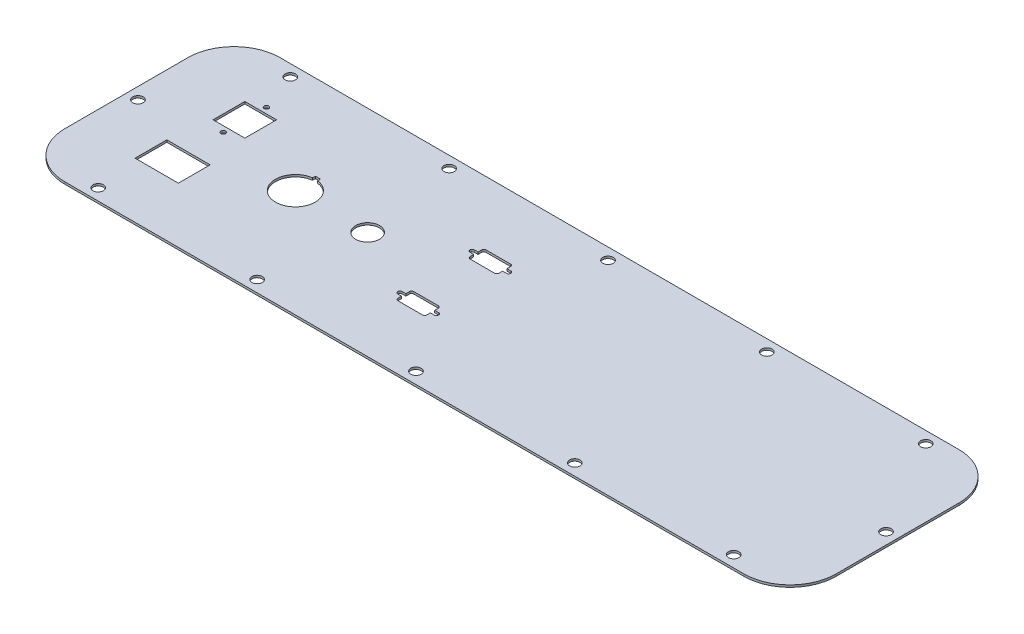
SolidWorks part; units mm, degrees
ref_plane "Front Plane" through (0, 0, 0) normal (0, 0, 1) x (1, 0, 0)
ref_plane "Top Plane" through (0, 0, 0) normal (0, 1, 0) x (1, 0, 0)
ref_plane "Right Plane" through (0, 0, 0) normal (1, 0, 0) x (0, 0, -1)
sketch "Sketch1" plane through (0, 0, 0) normal (0, 1, 0) x (1, 0, 0)
  line L0 (0, 0) -> (-259, 0) construction
  line L1 (235, -74.5) -> (-235, -74.5)
  line L2 (267, -42.5) -> (267, 42.5)
  line L3 (235, 74.5) -> (-235, 74.5)
  line L4 (-267, -42.5) -> (-267, 42.5)
  line L5 (267, -74.5) -> (-267, 74.5) construction
  line L6 (267, 74.5) -> (-267, -74.5) construction
  line L7 (0, 0) -> (259, 0) construction
  line L8 (220, 66.5) -> (-220, 66.5) construction
  line L9 (0, 66.5) -> (0, 0) construction
  line L10 (-220, 66.5) -> (-110, 66.5) construction
  arc A0 (-235, -74.5) -> (-267, -42.5) centre (-235, -42.5) cw
  arc A1 (267, -42.5) -> (235, -74.5) centre (235, -42.5) cw
  arc A2 (235, 74.5) -> (267, 42.5) centre (235, 42.5) cw
  arc A3 (-235, 74.5) -> (-267, 42.5) centre (-235, 42.5) ccw
  circle A4 centre (-259, 0) radius 3.6
  circle A5 centre (259, 0) radius 3.6
  circle A6 centre (-220, 66.5) radius 3.6
  circle A7 centre (-110, 66.5) radius 3.6
  circle A8 centre (0, 66.5) radius 3.6
  circle A9 centre (110, 66.5) radius 3.6
  circle A10 centre (220, 66.5) radius 3.6
  circle A11 centre (220, -66.5) radius 3.6
  circle A12 centre (110, -66.5) radius 3.6
  circle A13 centre (0, -66.5) radius 3.6
  circle A14 centre (-110, -66.5) radius 3.6
  circle A15 centre (-220, -66.5) radius 3.6
  point P0 (0, 0)
  point P26 (0, 66.5)
  dimension "D3" = 32
  dimension "D4" = 7.2
  dimension "D1" = 534
  dimension "D2" = 149
  dimension "D5" = 259
  dimension "D6" = 66.5
  dimension "D7" = 440
  dimension "D9" = 110
  dimension "D8" = 5
extrude "Boss-Extrude1" add sketch "Sketch1" along normal blind 1.5
sketch "Sketch2" plane through (0, 0, 0) normal (0, 1, 0) x (1, 0, 0)
  line L0 (-210, 25) -> (-210, -25) construction
  line L1 (-221, 14) -> (-199, 14)
  line L2 (-221, 14) -> (-221, 36)
  line L3 (-221, 36) -> (-199, 36)
  line L4 (-199, 14) -> (-199, 36)
  line L5 (-221, 14) -> (-199, 36) construction
  line L6 (-221, 36) -> (-199, 14) construction
  line L7 (-210, 10) -> (-210, 40) construction
  line L8 (-210, 14) -> (-210, 36) construction
  line L9 (-150, 0) -> (-150, 15.6382) construction
  line L10 (-210, -14) -> (-210, -36) construction
  line L11 (-151.75, 15.6382) -> (-148.25, 15.6382)
  line L12 (-151.75, 15.6382) -> (-151.75, 13.6382)
  line L14 (-148.25, 15.6382) -> (-148.25, 13.6382)
  line L15 (-195, -36) -> (-225, -36)
  line L16 (-195, -36) -> (-195, -14)
  line L17 (-195, -14) -> (-225, -14)
  line L18 (-225, -36) -> (-225, -14)
  line L19 (-195, -36) -> (-225, -14) construction
  line L20 (-195, -14) -> (-225, -36) construction
  line L21 (-40, 25) -> (-40, -25) construction
  line L23 (-210, 0) -> (0, 0) construction
  circle A0 centre (-210, 10) radius 1.6
  circle A1 centre (-210, 40) radius 1.6
  arc A2 (-151.75, 13.6382) -> (-148.25, 13.6382) centre (-150, 0) ccw
  arc A3 (-151.75, 13.6382) -> (-148.25, 13.6382) centre (-150, 0) cw construction
  circle A4 centre (-100, 0) radius 8.25
  point P0 (-210, 25)
  point P11 (-210, 25)
  point P22 (-150, 15.6382)
  point P32 (-210, 25)
  point P33 (-210, 0)
  point P37 (-40, 0)
  point P38 (-53.1341, 25)
  line B0 (-40, 19.5) -> (-40, 30.5) construction
  line B1 (-31.5, 30.5) -> (-48.5, 30.5)
  line B2 (-48.5, 19.5) -> (-31.5, 19.5)
  line B3 (-40, 25) -> (-50, 25) construction
  line B4 (-52.6, 26.5) -> (-50, 26.5)
  line B5 (-52.6, 23.5) -> (-50, 23.5)
  line B6 (-50, 23.5) -> (-50, 21)
  line B7 (-50, 26.5) -> (-50, 29)
  line B8 (-30, 23.5) -> (-30, 21)
  line B9 (-27.4, 23.5) -> (-30, 23.5)
  line B10 (-27.4, 26.5) -> (-30, 26.5)
  line B11 (-30, 26.5) -> (-30, 29)
  arc B12 (-52.6, 26.5) -> (-52.6, 23.5) centre (-52.6, 25) ccw
  arc B13 (-50, 21) -> (-48.5, 19.5) centre (-48.5, 21) ccw
  arc B14 (-48.5, 30.5) -> (-50, 29) centre (-48.5, 29) ccw
  arc B15 (-30, 21) -> (-31.5, 19.5) centre (-31.5, 21) cw
  arc B16 (-27.4, 26.5) -> (-27.4, 23.5) centre (-27.4, 25) cw
  arc B17 (-31.5, 30.5) -> (-30, 29) centre (-31.5, 29) cw
  line B18 (-31.5, -19.5) -> (-48.5, -19.5)
  line B19 (-48.5, -30.5) -> (-31.5, -30.5)
  line B20 (-40, -25) -> (-50, -25) construction
  line B21 (-52.6, -23.5) -> (-50, -23.5)
  line B22 (-52.6, -26.5) -> (-50, -26.5)
  line B23 (-50, -26.5) -> (-50, -29)
  line B24 (-50, -23.5) -> (-50, -21)
  line B25 (-30, -26.5) -> (-30, -29)
  line B26 (-27.4, -26.5) -> (-30, -26.5)
  line B27 (-27.4, -23.5) -> (-30, -23.5)
  line B28 (-30, -23.5) -> (-30, -21)
  arc B29 (-52.6, -23.5) -> (-52.6, -26.5) centre (-52.6, -25) ccw
  arc B30 (-50, -29) -> (-48.5, -30.5) centre (-48.5, -29) ccw
  arc B31 (-48.5, -19.5) -> (-50, -21) centre (-48.5, -21) ccw
  arc B32 (-30, -29) -> (-31.5, -30.5) centre (-31.5, -29) cw
  arc B33 (-27.4, -23.5) -> (-27.4, -26.5) centre (-27.4, -25) cw
  arc B34 (-31.5, -19.5) -> (-30, -21) centre (-31.5, -21) cw
  dimension "D4" = 3.2
  dimension "D6" = 27.5
  dimension "D13" = 16.5
  dimension "D1" = 22
  dimension "D2" = 22
  dimension "D3" = 210
  dimension "D5" = 30
  dimension "D7" = 3.5
  dimension "D8" = 2
  dimension "D9" = 50
  dimension "D10" = 30
  dimension "D11" = 22
  dimension "D12" = 150
  dimension "D14" = 100
  dimension "D15" = 50
  dimension "D16" = 40
sketch_block_instance "DB9-cutout-1"
sketch_block "DB9-cutout" parameters "D4"=1.5, "D1"=11, "D2"=10, "D3"=3
sketch_block_instance "DB9-cutout-2"
extrude "Cut-Extrude1" cut sketch "Sketch2" along normal through all
ref_plane "Plane1" through (-210, 0, 0) normal (1, 0, 0) x (0, 0, -1)
ref_plane "Plane2" through (-150, 0, 0) normal (1, 0, 0) x (0, 0, -1)
ref_plane "Plane3" through (-210, 0, 0) normal (1, 0, 0) x (0, 0, -1)
ref_plane "Plane4" through (0, 0, 25) normal (0, 0, 1) x (1, 0, 0)
ref_plane "Plane5" through (0, 0, -25) normal (0, 0, 1) x (1, 0, 0)
ref_plane "Plane6" through (0, 0, 25) normal (0, 0, 1) x (1, 0, 0)
ref_plane "Plane7" through (0, 0, -25) normal (0, 0, 1) x (1, 0, 0)
ref_plane "Plane8" through (-40, 0, 0) normal (1, 0, 0) x (0, 0, -1)
